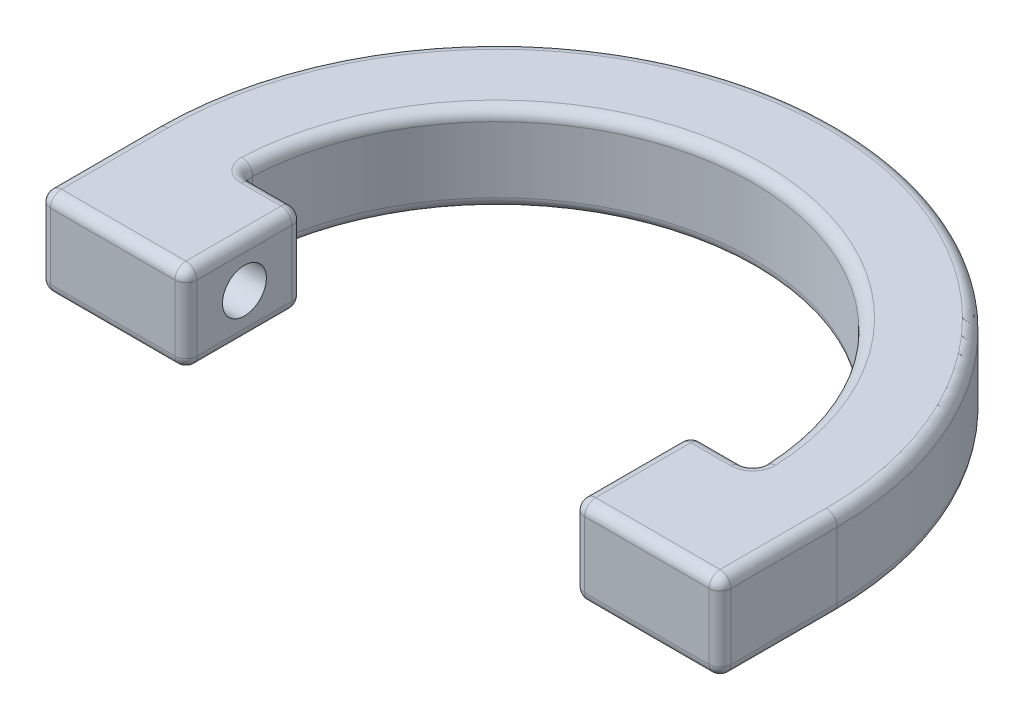
SolidWorks part; units mm, degrees
material "ABS"
ref_plane "Plan de face" through (0, 0, 0) normal (0, 0, 1) x (1, 0, 0)
ref_plane "Plan de dessus" through (0, 0, 0) normal (0, 1, 0) x (1, 0, 0)
ref_plane "Plan de droite" through (0, 0, 0) normal (1, 0, 0) x (0, 0, -1)
ref_plane "Plan1" through (0, -27.53, 0) normal (0, 1, 0) x (-1, 0, 0)
sketch "Esquisse1" plane through (0, -27.53, 0) normal (0, 1, 0) x (-1, 0, 0)
  line L1 (-23.9978, -61.1337) -> (-13.9978, -61.1337)
  line L2 (-23.9978, -61.1337) -> (-23.9978, -69.1337)
  line L3 (-18.2478, -69.1337) -> (-13.9978, -69.1337)
  line L4 (-13.9978, -61.1337) -> (-13.9978, -69.1337)
  line L8 (-0.7478, -61.3362) -> (-0.7478, -7.25) construction
  line L13 (12.5022, -61.1337) -> (12.5022, -69.1337)
  line L14 (16.7522, -69.1337) -> (12.5022, -69.1337)
  line L15 (22.5022, -61.1337) -> (22.5022, -69.1337)
  line L16 (22.5022, -61.1337) -> (12.5022, -61.1337)
  line L17 (-10.8248, -64.0645) -> (-16.7854, -64.0645) construction
  arc A2 (-23.9978, -69.1337) -> (22.5022, -69.1337) centre (-0.7478, -69.1337) ccw
  arc A3 (-18.2478, -69.1337) -> (16.7522, -69.1337) centre (-0.7478, -69.1337) ccw
  point P0 (-13.4507, -62.8338)
  point P22 (11.9551, -62.8338)
  dimension "D1" = 26.5
  dimension "D2" = 17.5
  dimension "D3" = 23.25
  dimension "D5" = 10
  dimension "D9" = 8
extrude "Boss.-Extru.1" add sketch "Esquisse1" along normal blind 6
fillet "Congé1" radius 0.75 28 edges at (23.9978, -27.53, -65.1337) (-12.5022, -27.53, -65.1337) (-14.6272, -27.53, -69.1337) (-12.5022, -24.53, -69.1337) (-16.7522, -24.53, -69.1337) (16.1228, -27.53, -69.1337) (23.9978, -24.53, -61.1337) (18.9978, -27.53, -61.1337) (23.9978, -21.53, -65.1337) (18.9978, -21.53, -61.1337) (13.9978, -24.53, -61.1337) (13.9978, -27.53, -65.1337) (13.9978, -24.53, -69.1337) (16.1228, -21.53, -69.1337) (18.2478, -24.53, -69.1337) (13.9978, -21.53, -65.1337) (-17.5022, -27.53, -61.1337) (-12.5022, -24.53, -61.1337) (-17.5022, -21.53, -61.1337) (-22.5022, -24.53, -61.1337) (-22.5022, -27.53, -65.1337) (0.7478, -27.53, -86.6337) (0.7478, -27.53, -92.3837) (-22.5022, -21.53, -65.1337) (-12.5022, -21.53, -65.1337) (-14.6272, -21.53, -69.1337) (0.7478, -21.53, -92.3837) (0.7478, -21.53, -86.6337)
sketch "Esquisse2" plane through (-12.5022, 0, 0) normal (1, 0, 0) x (0, 0, -1)
  line L2 (61.8837, -21.53) -> (68.3837, -21.53) construction
  line L4 (61.1337, -26.78) -> (61.1337, -22.28) construction
  circle A0 centre (65.1337, -24.53) radius 1.5
  dimension "D1" = 3
  dimension "D2" = 4
  dimension "D3" = 3
extrude "Enlèv. mat.-Extru.1" cut sketch "Esquisse2" against normal blind 6
sketch "Esquisse3" plane through (13.9978, 0, 0) normal (-1, 0, 0) x (0, 0, 1)
  line L3 (-68.3837, -21.53) -> (-61.8837, -21.53) construction
  line L4 (-61.1337, -22.28) -> (-61.1337, -26.78) construction
  circle A0 centre (-65.1337, -24.53) radius 1.5
  dimension "D1" = 3
  dimension "D2" = 3
  dimension "D3" = 4
extrude "Enlèv. mat.-Extru.2" cut sketch "Esquisse3" against normal blind 6
